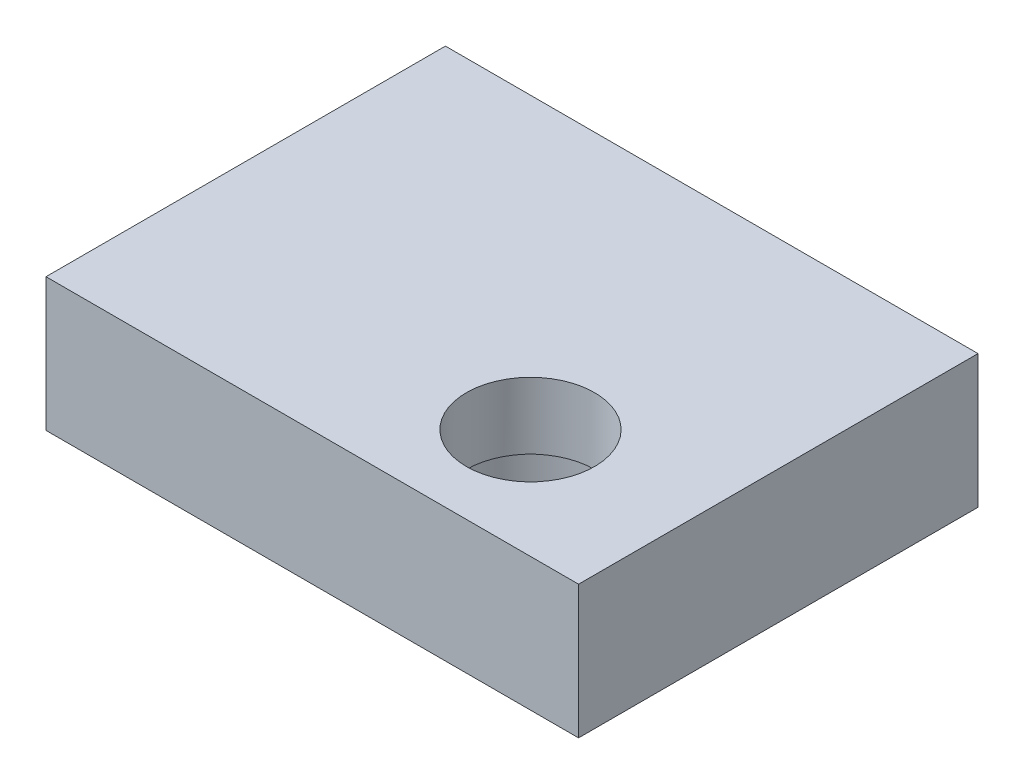
SolidWorks part; units mm, degrees
material "PLA"
ref_plane "Front Plane" through (0, 0, 0) normal (0, 0, 1) x (1, 0, 0)
ref_plane "Top Plane" through (0, 0, 0) normal (0, 1, 0) x (1, 0, 0)
ref_plane "Right Plane" through (0, 0, 0) normal (1, 0, 0) x (0, 0, -1)
sketch "Sketch1" plane through (0, 0, 0) normal (0, 1, 0) x (1, 0, 0)
  line L1 (-20, -15) -> (20, -15)
  line L2 (-20, -15) -> (-20, 15)
  line L3 (-20, 15) -> (20, 15)
  line L4 (20, -15) -> (20, 15)
  line L5 (-20, -15) -> (20, 15) construction
  line L6 (-20, 15) -> (20, -15) construction
  point P0 (0, 0)
  dimension "D1" = 40
  dimension "D2" = 30
extrude "Boss-Extrude1" add sketch "Sketch1" along normal blind 10
sketch "Sketch2" plane through (0, 0, 0) normal (0, -1, 0) x (-1, 0, 0)
  line L0 (20, 0) -> (-20, 0) construction
  line L1 (20, 15) -> (20, -15) construction
  line L2 (-20, -15) -> (-20, 15) construction
  line L3 (-20, -15) -> (20, 15) construction
  line L4 (20, -15) -> (-20, 15) construction
  line L5 (0, -15) -> (0, 15) construction
  line L6 (20, -15) -> (-20, -15) construction
  line L7 (-20, 15) -> (20, 15) construction
  circle A0 centre (13.3333, -10) radius 2
  circle A1 centre (13.3333, 10) radius 2
  circle A2 centre (-13.3333, 10) radius 2
  circle A3 centre (-8.14, -6.75) radius 6.25
  dimension "D1" = 4
  dimension "D3" = 12.5
  dimension "D2" = 5
  dimension "D4" = 11.86
  dimension "D5" = 8.25
extrude "Cut-Extrude1" cut sketch "Sketch2" against normal blind 5
sketch "Sketch3" plane through (0, 10, 0) normal (0, 1, 0) x (1, 0, 0)
  line L0 (20, -15) -> (20, 15) construction
  line L1 (-20, -15) -> (20, -15) construction
  circle A0 centre (8.14, -6.75) radius 4.8125
  dimension "D1" = 9.625
  dimension "D2" = 11.86
  dimension "D3" = 8.25
extrude "Cut-Extrude2" cut sketch "Sketch3" against normal up to surface (10 mm away) up to face at (8.14, 0, 0.5)
